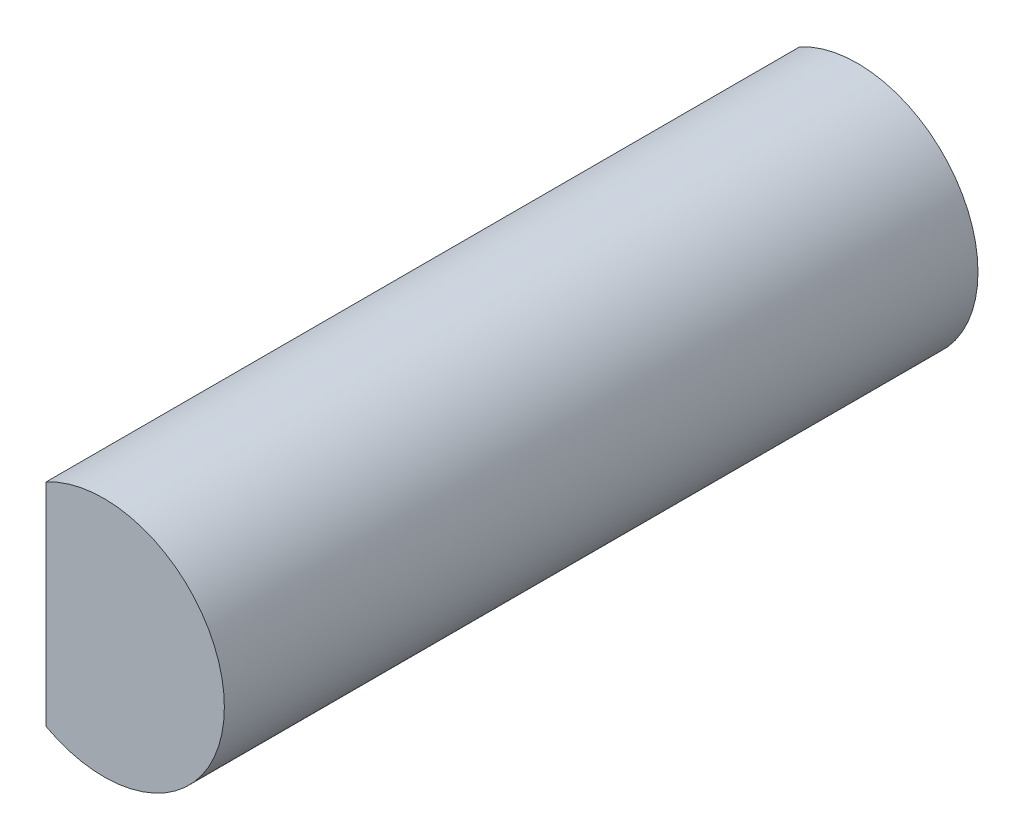
SolidWorks part; units mm, degrees
ref_plane "Front Plane" through (0, 0, 0) normal (0, 0, 1) x (1, 0, 0)
ref_plane "Top Plane" through (0, 0, 0) normal (0, 1, 0) x (1, 0, 0)
ref_plane "Right Plane" through (0, 0, 0) normal (1, 0, 0) x (0, 0, -1)
sketch "Sketch1" plane through (0, 0, 0) normal (0, 0, 1) x (1, 0, 0)
  line L0 (0, 0) -> (0, 5) construction
  line L1 (0, 0) -> (-2.5, 4.3301) construction
  line L2 (-2.5, 4.3301) -> (-2.5, -4.3301) construction
  line L3 (-2.3, 4.2131) -> (-2.3, -4.2131)
  line L4 (-0.2, 0.7464) -> (-2.3268, 4.4301) construction
  line L5 (-0.2, 0.7464) -> (-0.2, 5) construction
  arc A0 (-2.5, -4.3301) -> (-2.5, 4.3301) centre (0, 0) ccw construction
  arc A1 (-2.3, -4.2131) -> (-2.3, 4.2131) centre (0, 0) ccw
  dimension "D1" = 10
  dimension "D2" = 30
  dimension "D3" = 0.2
extrude "Boss-Extrude1" add sketch "Sketch1" along normal blind 30
